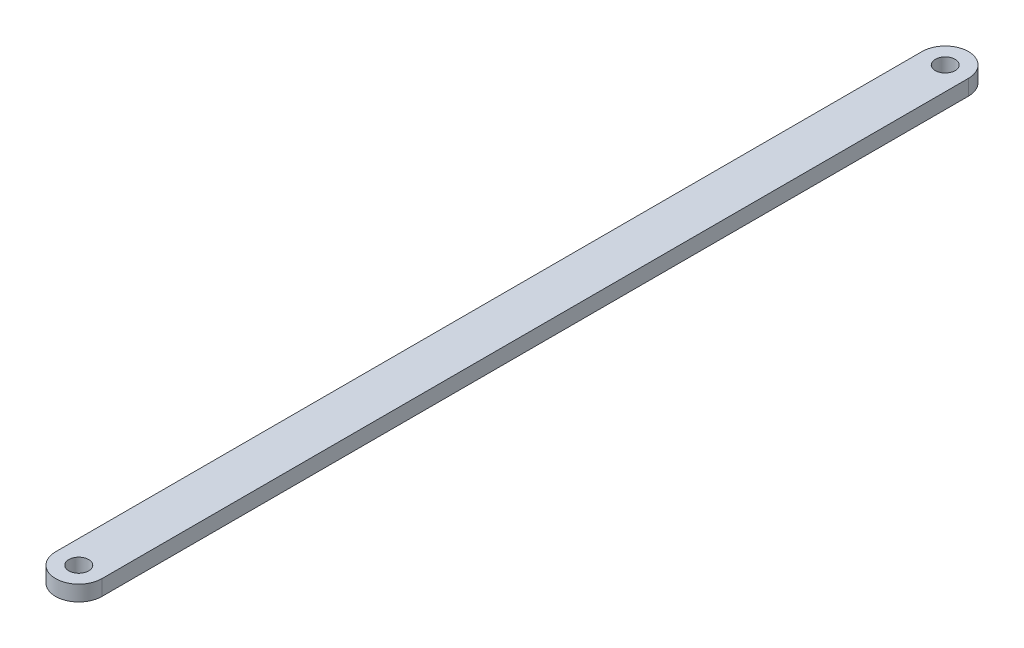
SolidWorks part; units mm, degrees
ref_plane "Front Plane" through (0, 0, 0) normal (0, 0, 1) x (1, 0, 0)
ref_plane "Top Plane" through (0, 0, 0) normal (0, 1, 0) x (1, 0, 0)
ref_plane "Right Plane" through (0, 0, 0) normal (1, 0, 0) x (0, 0, -1)
sketch "Sketch1" plane through (0, 0, 0) normal (0, 1, 0) x (1, 0, 0)
  line L0 (0, 0) -> (0, 177.8) construction
  line L1 (-4.7625, 0) -> (-4.7625, 177.8)
  line L2 (4.7625, 0) -> (4.7625, 177.8)
  arc A0 (-4.7625, 0) -> (4.7625, 0) centre (0, 0) ccw
  arc A1 (4.7625, 177.8) -> (-4.7625, 177.8) centre (0, 177.8) ccw
  circle A2 centre (0, 177.8) radius 2.032
  circle A3 centre (0, 0) radius 2.032
  point P3 (0, 88.9)
  dimension "D1" = 4.7625
  dimension "D3" = 4.064
  dimension "D4" = 4.064
  dimension "D2" = 177.8
extrude "Boss-Extrude1" add sketch "Sketch1" along normal blind 3.175
